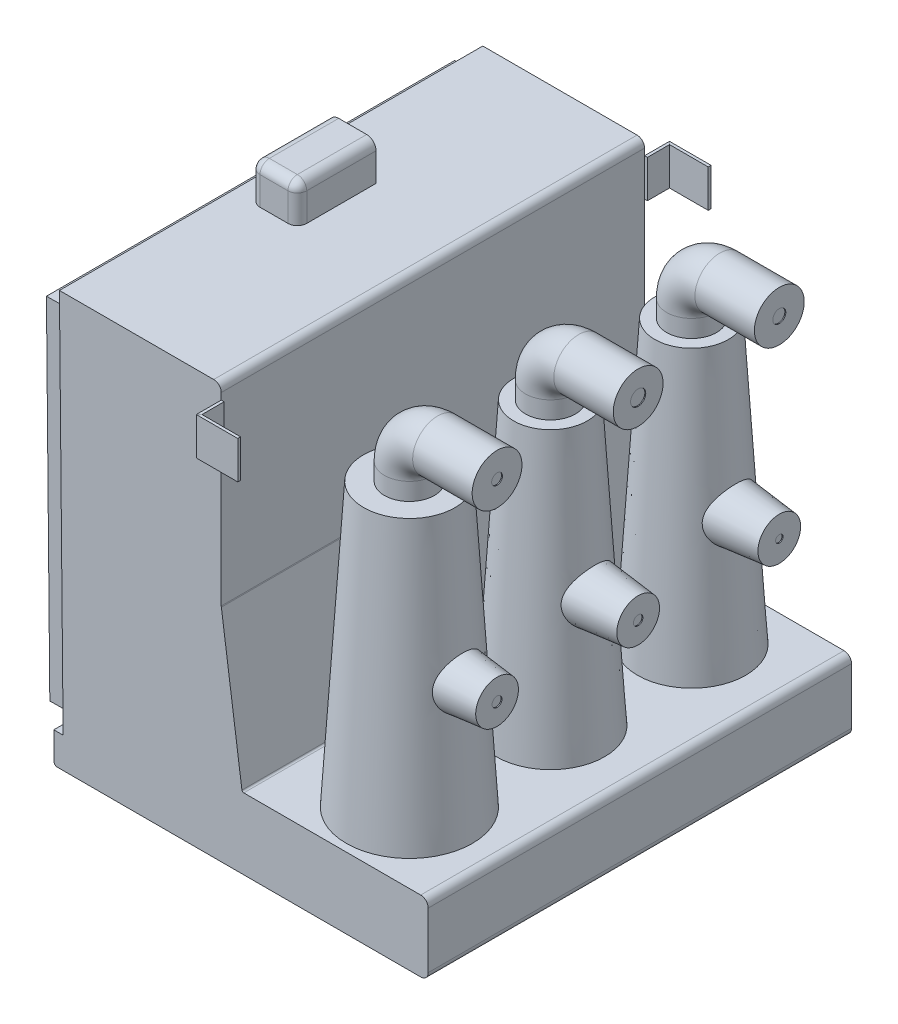
SolidWorks part; units mm, degrees
ref_plane "Alzado" through (0, 0, 0) normal (0, 0, 1) x (1, 0, 0)
ref_plane "Planta" through (0, 0, 0) normal (0, 1, 0) x (1, 0, 0)
ref_plane "Vista lateral" through (0, 0, 0) normal (1, 0, 0) x (0, 0, -1)
sketch "Croquis1" plane through (0, 0, 0) normal (0, 0, 1) x (1, 0, 0)
  line L0 (2.0023, 435.9953) -> (165.9857, 435.9953)
  line L1 (173.995, 427.986) -> (173.995, 231.5011)
  line L2 (174.137, 230.4444) -> (195.9953, 73.02)
  line L3 (197.9604, 71.4251) -> (386.006, 71.4251)
  line L4 (4.3817, 190.8398) -> (307.3817, 190.8398) construction
  line L5 (394.0153, 63.4158) -> (394.0153, 4.0047)
  line L6 (386.006, -4.0047) -> (0, -4.0047)
  line L7 (-4.0047, 0) -> (-4.0047, 28.5331)
  line L8 (-4.0047, 28.5331) -> (5.9569, 28.5331)
  line L9 (5.9569, 28.5331) -> (2.0023, 435.9953)
  arc A0 (165.9857, 435.9953) -> (173.995, 427.986) centre (165.9857, 427.986) cw
  arc A1 (173.995, 231.5011) -> (174.137, 230.4444) centre (177.9997, 231.5011) ccw
  arc A3 (195.9953, 73.02) -> (197.9604, 71.4251) centre (197.8321, 73.2751) ccw
  arc A5 (386.006, 71.4251) -> (394.0153, 63.4158) centre (386.006, 63.4158) cw
  arc A7 (394.0153, 4.0047) -> (386.006, -4.0047) centre (386.006, 4.0047) cw
  arc A8 (0, -4.0047) -> (-4.0047, 0) centre (0, 0) cw
  dimension "D1" = 440
  dimension "D2" = 170
  dimension "D3" = 198.02
  dimension "D4" = 398.02
  dimension "D5" = 9.9616
  dimension "D6" = 303
extrude "Saliente-Extruir2" add sketch "Croquis1" along normal blind 450
sketch "Croquis3" plane through (0, 71.4251, 0) normal (0, 1, 0) x (1, 0, 0)
  line L0 (-4.0047, -225) -> (298.9953, -225) construction
  line L1 (-4.0047, -450) -> (-4.0047, 0) construction
  line L2 (298.9953, -225) -> (298.9953, -375) construction
  line L3 (298.9953, -225) -> (298.9953, -75) construction
  circle A0 centre (298.9953, -375) radius 67
  circle A1 centre (298.9953, -225) radius 57.5
  circle A2 centre (298.9953, -75) radius 57.5
  dimension "D4" = 115
  dimension "D5" = 115
  dimension "D6" = 134
  dimension "D1" = 303
  dimension "D2" = 150
  dimension "D3" = 150
extrude "Saliente-Extruir3" add sketch "Croquis3" along normal blind 300 draft 3.5
sketch "Croquis4" plane through (0, 371.4251, 0) normal (0, 1, 0) x (1, 0, 0)
  line L1 (298.9953, -423.6512) -> (298.9953, -35.8488) construction
  circle A3 centre (298.9953, -375) radius 48.6512 construction
  circle A4 centre (298.9953, -75) radius 39.1512 construction
ref_plane "Plano1" through (298.9953, 0, 0) normal (1, 0, 0) x (0, 0, -1)
sketch "Croquis5" plane through (298.9953, 0, 0) normal (1, 0, 0) x (0, 0, -1)
  line L0 (-341.5665, 71.4251) -> (-282.5, 71.4251) construction
  line L1 (-375, 419.9251) -> (-75, 419.9251) construction
  line L3 (-282.5, 71.4251) -> (-341.5665, 71.4251) construction
  line L4 (-225, 214.9251) -> (-225, -4.0047) construction
  line L5 (-225, 214.9251) -> (-375, 214.9251) construction
  line L6 (-375, 214.9251) -> (-375, 260.4075) construction
  line L7 (-225, 214.9251) -> (-75, 214.9251) construction
  line L8 (-75, 214.9251) -> (-75, 286.5313) construction
  line L9 (-326.3488, 371.4251) -> (-423.6512, 371.4251) construction
  line L10 (-423.6512, 371.4251) -> (-375, 371.4251) construction
  line L11 (-375, 371.4251) -> (-375, 214.9251) construction
  line L12 (-114.1512, 371.4251) -> (-35.8488, 371.4251) construction
  line L13 (-35.8488, 371.4251) -> (-75, 371.4251) construction
  line L14 (-75, 371.4251) -> (-75, 214.9251) construction
  line L15 (-450, -4.0047) -> (0, -4.0047) construction
  line L17 (-225, 214.9251) -> (-225, 419.9251) construction
  line L18 (-450, 71.4251) -> (0, 71.4251) construction
  circle A0 centre (-225, 214.9251) radius 32.5
  circle A1 centre (-375, 214.9251) radius 32.5
  circle A2 centre (-75, 214.9251) radius 32.5
  circle A3 centre (-225, 419.9251) radius 12.5
  circle A4 centre (-375, 419.9251) radius 12.5
  circle A5 centre (-75, 419.9251) radius 12.5
  dimension "D2" = 65
  dimension "D3" = 65
  dimension "D4" = 65
  dimension "D5" = 25
  dimension "D6" = 25
  dimension "D7" = 25
  dimension "D8" = 348.5
  dimension "D9" = 205
extrude "Saliente-Extruir6" add sketch "Croquis5" along normal blind 93.19 draft 6
sketch "Croquis7" plane through (6.2333, 0.0605, 0) normal (-1, -0.0097, 0) x (0, 0, 1)
  line L0 (450, 435.9554) -> (0, 435.9554) construction
  line L1 (8, 45.0745) -> (442, 45.0745)
  line L2 (8, 45.0745) -> (8, 415.9554)
  line L3 (8, 415.9554) -> (442, 415.9554)
  line L4 (442, 45.0745) -> (442, 415.9554)
  line L5 (8, 45.0745) -> (442, 415.9554) construction
  line L6 (8, 415.9554) -> (442, 45.0745) construction
  line L7 (450, 435.9554) -> (450, 28.474) construction
  line L8 (0, 435.9554) -> (0, 28.474) construction
  point P0 (225, 230.515)
  dimension "D1" = 20
  dimension "D2" = 8
  dimension "D3" = 8
extrude "Saliente-Extruir7" add sketch "Croquis7" along normal blind 22
sketch "Croquis8" plane through (0, 371.4251, 0) normal (0, 1, 0) x (1, 0, 0)
  line L0 (298.9953, -375) -> (395.9362, -375) construction
  line L1 (259.8441, -225) -> (392.1853, -225) construction
  line L2 (392.1853, -227.7053) -> (392.1853, -222.2947) construction
  line L3 (259.8441, -75) -> (388.9953, -75) construction
  circle A0 centre (298.9953, -225) radius 39.1512 construction
  circle A1 centre (298.9953, -75) radius 39.1512 construction
ref_plane "Plano2" through (0, 0, 375) normal (0, 0, 1) x (1, 0, 0)
ref_plane "Plano3" through (0, 0, 225) normal (0, 0, 1) x (1, 0, 0)
ref_plane "Plano4" through (0, 0, 75) normal (0, 0, 1) x (1, 0, 0)
sketch "Croquis9" plane through (0, 435.9953, 0) normal (0, 1, 0) x (1, 0, 0)
  line L0 (2.0023, -225) -> (22.0023, -225) construction
  line L1 (2.0023, -450) -> (2.0023, 0) construction
  line L4 (71.7626, -183.1696) -> (22.0023, -183.1696)
  line L5 (71.7626, -183.1696) -> (71.7626, -266.8304)
  line L6 (71.7626, -266.8304) -> (22.0023, -266.8304)
  line L7 (22.0023, -183.1696) -> (22.0023, -266.8304)
  line L8 (71.7626, -183.1696) -> (22.0023, -266.8304) construction
  line L9 (71.7626, -266.8304) -> (22.0023, -183.1696) construction
  point P6 (46.8824, -225)
  dimension "D1" = 20
extrude "Saliente-Extruir8" add sketch "Croquis9" along normal blind 40
fillet "Redondeo1" radius 10 5 edges at (22.0023, 475.9953, 225) (22.0023, 455.9953, 266.8304) (46.8824, 475.9953, 266.8304) (71.7626, 455.9953, 266.8304) (71.7626, 475.9953, 225)
sketch "Croquis10" plane through (0, 0, 450) normal (0, 0, 1) x (1, 0, 0)
  line L0 (165.9857, 435.9953) -> (2.0023, 435.9953) construction
  line L1 (173.995, 380.9953) -> (176.995, 380.9953)
  line L2 (173.995, 380.9953) -> (173.995, 420.9953)
  line L3 (173.995, 420.9953) -> (176.995, 420.9953)
  line L4 (176.995, 380.9953) -> (176.995, 420.9953)
  line L5 (173.995, 380.9953) -> (176.995, 420.9953) construction
  line L6 (173.995, 420.9953) -> (176.995, 380.9953) construction
  line L8 (173.995, 231.5011) -> (173.995, 427.986) construction
  point P0 (175.495, 400.9953)
  dimension "D1" = 3
  dimension "D2" = 40
  dimension "D3" = 15
sketch3d "Croquis3D1"
  line L0 (175.495, 400.9953, 450) -> (175.495, 400.9953, 475)
  line L1 (175.495, 400.9953, 475) -> (218.0943, 400.9953, 475)
  dimension "D1" = 25
sweep "Barrer1" add profiles "Croquis10" path "Croquis3D1"
mirror "Simetría2" about plane through (0, 0, 225) normal (0, 0, 1) of "Barrer1"
sketch "Croquis11" plane through (0, 0, 0) normal (0, 0, -1) x (-1, 0, 0)
  line L0 (-173.995, 420.9953) -> (-176.995, 420.9953)
  line L1 (-176.995, 420.9953) -> (-176.995, 380.9953)
  line L2 (-176.995, 380.9953) -> (-173.995, 380.9953)
  line L3 (-173.995, 380.9953) -> (-173.995, 420.9953)
  line L4 (-176.995, 420.9953) -> (-173.995, 380.9953) construction
  line L5 (-173.995, 420.9953) -> (-176.995, 380.9953) construction
sketch3d "Croquis3D3"
  line L0 (175.495, 400.9953, 0) -> (175.495, 400.9953, -25)
  line L1 (176.995, 420.9953, 0) -> (173.995, 380.9953, 0) construction
  line L2 (175.495, 400.9953, -25) -> (218.1367, 400.9953, -25)
  dimension "D1" = 25
sweep "Barrer2" add profiles "Croquis11" path "Croquis3D3"
ref_plane "Plano5" through (0, 241.4251, 0) normal (0, 1, 0) x (1, 0, 0)
sketch "Croquis15" plane through (0, 71.4251, 0) normal (0, 1, 0) x (1, 0, 0)
  line L0 (298.9953, -423.6512) -> (298.9953, -35.8488) construction
  line L1 (259.8441, -75) -> (388.9953, -75) construction
  circle A0 centre (298.9953, -375) radius 26.5
  circle A1 centre (298.9953, -225) radius 26.5
  circle A2 centre (298.9953, -75) radius 26.5
  dimension "D1" = 53
  dimension "D2" = 53
  dimension "D3" = 53
sketch3d "Croquis3D5"
  line L0 (298.9953, 71.4251, 375) -> (298.9953, 341.4336, 375)
  line L1 (298.9953, 371.4251, 375) -> (395.9362, 371.4251, 375) construction
  line L2 (392.1853, 419.9251, 375) -> (328.9953, 419.9251, 375)
  line L3 (298.9953, 419.9251, 375) -> (392.1853, 419.9251, 375) construction
  line L4 (298.9953, 389.9251, 375) -> (298.9953, 341.4336, 375)
  arc A0 (298.9953, 389.9251, 375) -> (328.9953, 419.9251, 375) centre (328.9953, 389.9251, 375) ccw
  point P8 (298.9953, 371.4251, 375)
  point P12 (298.9953, 419.9251, 375)
  point P13 (328.9953, 389.9251, 345)
  dimension "D1" = 30
sweep "Barrer7" add profiles "Croquis15" path "Croquis3D5"
ref_plane "Plano6" through (0, 0, 225) normal (0, 0, 1) x (1, 0, 0)
sketch "Croquis16" plane through (392.1853, 0, 0) normal (1, 0, 0) x (0, 0, -1)
  circle A0 centre (-375, 419.9251) radius 5.7549
  circle A1 centre (-225, 419.9251) radius 8.0609
  circle A2 centre (-75, 419.9251) radius 6.9295
  circle A3 centre (-375, 214.9251) radius 5.2681
  circle A4 centre (-225, 214.9251) radius 5.036
  circle A5 centre (-75, 214.9251) radius 3.9655
extrude "Cortar-Extruir1" cut sketch "Croquis16" against normal blind 1
